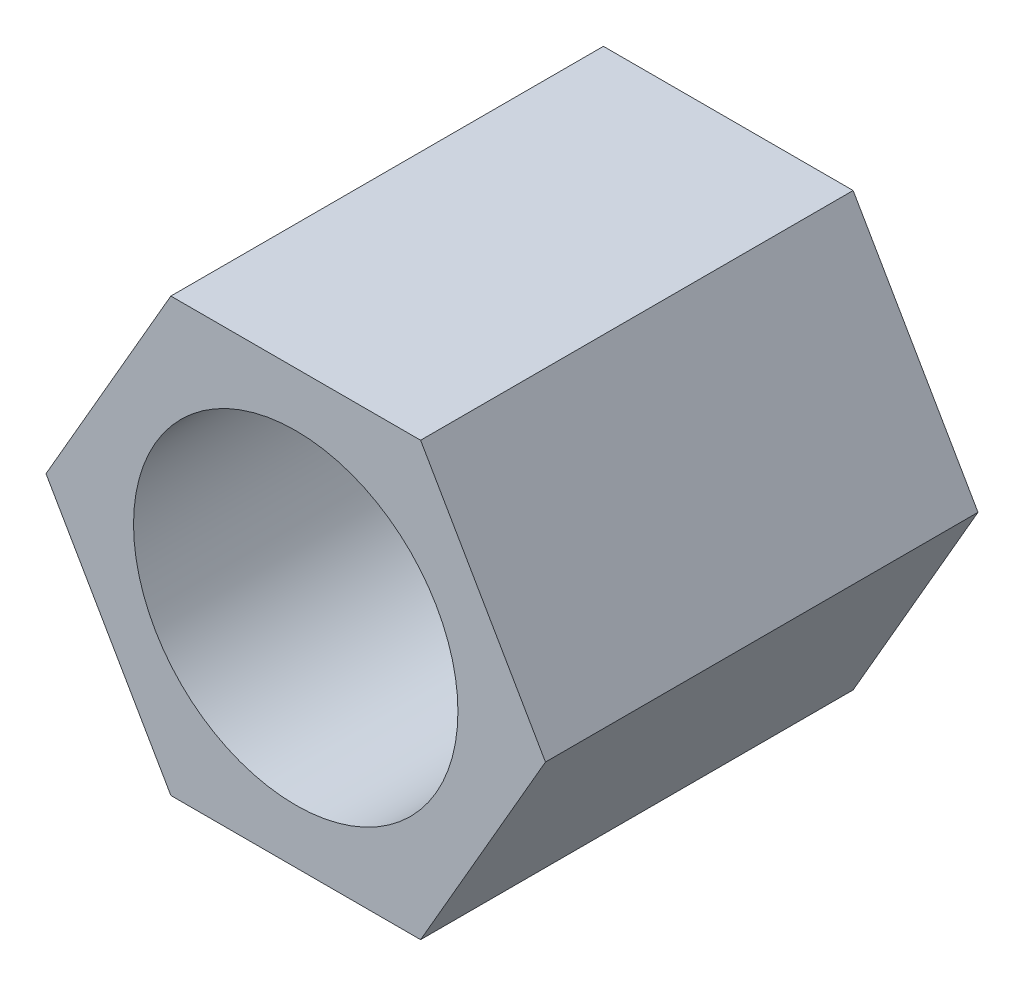
SolidWorks part; units mm, degrees
ref_plane "Front Plane" through (0, 0, 0) normal (0, 0, 1) x (1, 0, 0)
ref_plane "Top Plane" through (0, 0, 0) normal (0, 1, 0) x (1, 0, 0)
ref_plane "Right Plane" through (0, 0, 0) normal (1, 0, 0) x (0, 0, -1)
sketch "Sketch1" plane through (0, 0, 0) normal (0, 0, 1) x (1, 0, 0)
  line L1 (-2.3094, 4) -> (-4.6188, 0)
  line L2 (-4.6188, 0) -> (-2.3094, -4)
  line L3 (-2.3094, -4) -> (2.3094, -4)
  line L4 (2.3094, -4) -> (4.6188, 0)
  line L5 (4.6188, 0) -> (2.3094, 4)
  line L6 (2.3094, 4) -> (-2.3094, 4)
  circle A0 centre (0, 0) radius 4 construction
  dimension "D1" = 8
extrude "Boss-Extrude1" add sketch "Sketch1" along normal blind 8
sketch "Sketch2" plane through (0, 0, 8) normal (0, 0, 1) x (1, 0, 0)
  circle A0 centre (0, 0) radius 1.5
  dimension "D1" = 3
extrude "Cut-Extrude1" cut sketch "Sketch2" against normal through all
sketch "Sketch3" plane through (0, 0, 8) normal (0, 0, 1) x (1, 0, 0)
  circle A0 centre (0, 0) radius 3
  dimension "D1" = 6
extrude "Cut-Extrude2" cut sketch "Sketch3" against normal blind 6
